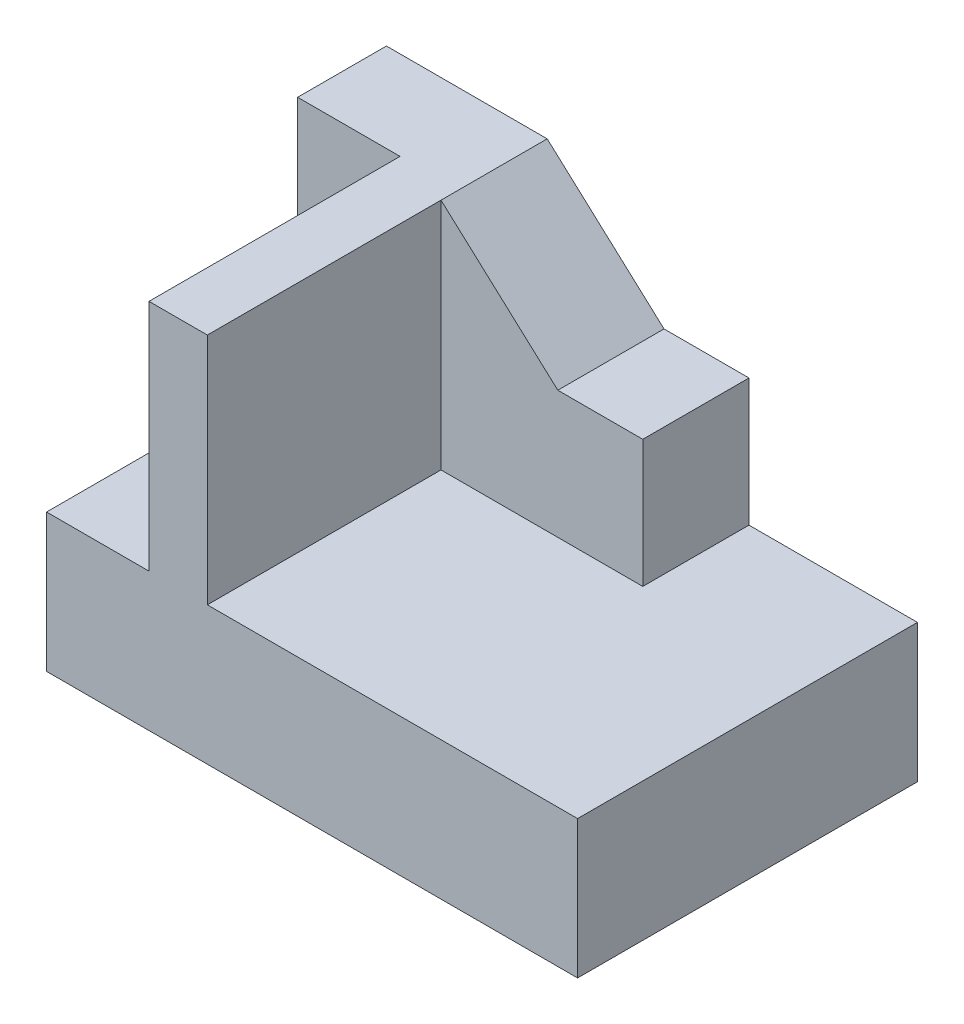
SolidWorks part; units mm, degrees
ref_plane "Front Plane" through (0, 0, 0) normal (0, 0, 1) x (1, 0, 0)
ref_plane "Top Plane" through (0, 0, 0) normal (0, 1, 0) x (1, 0, 0)
ref_plane "Right Plane" through (0, 0, 0) normal (1, 0, 0) x (0, 0, -1)
sketch "Sketch3" plane through (0, 0, 0) normal (0, 0, 1) x (1, 0, 0)
  line L1 (-17.7901, 11.0399) -> (32.2099, 11.0399)
  line L2 (-17.7901, 11.0399) -> (-17.7901, -1.9601)
  line L3 (-17.7901, -1.9601) -> (32.2099, -1.9601)
  line L4 (32.2099, 11.0399) -> (32.2099, -1.9601)
  dimension "D1" = 50
  dimension "D2" = 13
extrude "Boss-Extrude1" add sketch "Sketch3" against normal blind 32
sketch "Sketch4" plane through (0, 0, 0) normal (0, 0, 1) x (1, 0, 0)
  line L0 (-8.1462, 11.0399) -> (-8.1462, 33.0399)
  line L1 (32.2099, 11.0399) -> (-17.7901, 11.0399) construction
  line L2 (-8.1462, 33.0399) -> (-2.6504, 33.0399)
  line L3 (-2.6504, 33.0399) -> (-2.6504, 11.0399)
  line L4 (32.2099, 11.0399) -> (-2.6504, 11.0399)
  line L8 (-17.7901, 11.0399) -> (-17.7901, -1.9601)
  line L9 (-17.7901, -1.9601) -> (32.2099, -1.9601)
  line L10 (32.2099, -1.9601) -> (32.2099, 11.0399)
  line L11 (32.2099, 11.0399) -> (-17.7901, 11.0399)
  line L12 (-17.7901, 11.0399) -> (-17.7901, -1.9601)
  line L13 (-17.7901, -1.9601) -> (32.2099, -1.9601)
  line L14 (32.2099, -1.9601) -> (32.2099, 11.0399)
  line L15 (-8.1462, 11.0399) -> (-17.7901, 11.0399)
  dimension "D1" = 22
  dimension "D2" = 0
extrude "Boss-Extrude2" add sketch "Sketch4" against normal blind 32
sketch "Sketch5" plane through (0, 0, -32) normal (0, 0, -1) x (-1, 0, 0)
  line L0 (-16.3496, 11.0399) -> (-16.3496, 23.0399)
  line L1 (-32.2099, 11.0399) -> (2.6504, 11.0399) construction
  line L2 (-16.3496, 23.0399) -> (-8.3496, 23.0399)
  line L3 (-8.3496, 23.0399) -> (2.6504, 33.0399)
  line L4 (-16.3496, 11.0399) -> (2.6504, 11.0399)
  line L13 (17.7901, -1.9601) -> (17.7901, 11.0399)
  line L14 (17.7901, 11.0399) -> (8.1462, 11.0399)
  line L15 (8.1462, 11.0399) -> (8.1462, 33.0399)
  line L16 (8.1462, 33.0399) -> (2.6504, 33.0399)
  line L17 (2.6504, 33.0399) -> (2.6504, 11.0399)
  line L18 (2.6504, 11.0399) -> (-32.2099, 11.0399)
  line L19 (-32.2099, 11.0399) -> (-32.2099, -1.9601)
  line L20 (-32.2099, -1.9601) -> (17.7901, -1.9601)
  line L25 (2.6504, 33.0399) -> (2.6504, 11.0399)
  dimension "D1" = 12
  dimension "D2" = 8
  dimension "D3" = 19
  dimension "D4" = 0
extrude "Boss-Extrude3" add sketch "Sketch5" against normal blind 10
sketch "Sketch8" plane through (0, 11.0399, 0) normal (0, 1, 0) x (1, 0, 0)
  line L0 (-17.7901, 32) -> (-17.7901, 0) construction
  line L1 (-8.1462, 32) -> (-17.7901, 32)
  line L2 (-8.1462, 32) -> (-8.1462, 23.6403)
  line L3 (-8.1462, 23.6403) -> (-17.7901, 23.6403)
  line L4 (-17.7901, 32) -> (-17.7901, 23.6403)
extrude "Boss-Extrude4" add sketch "Sketch8" along normal blind 22
